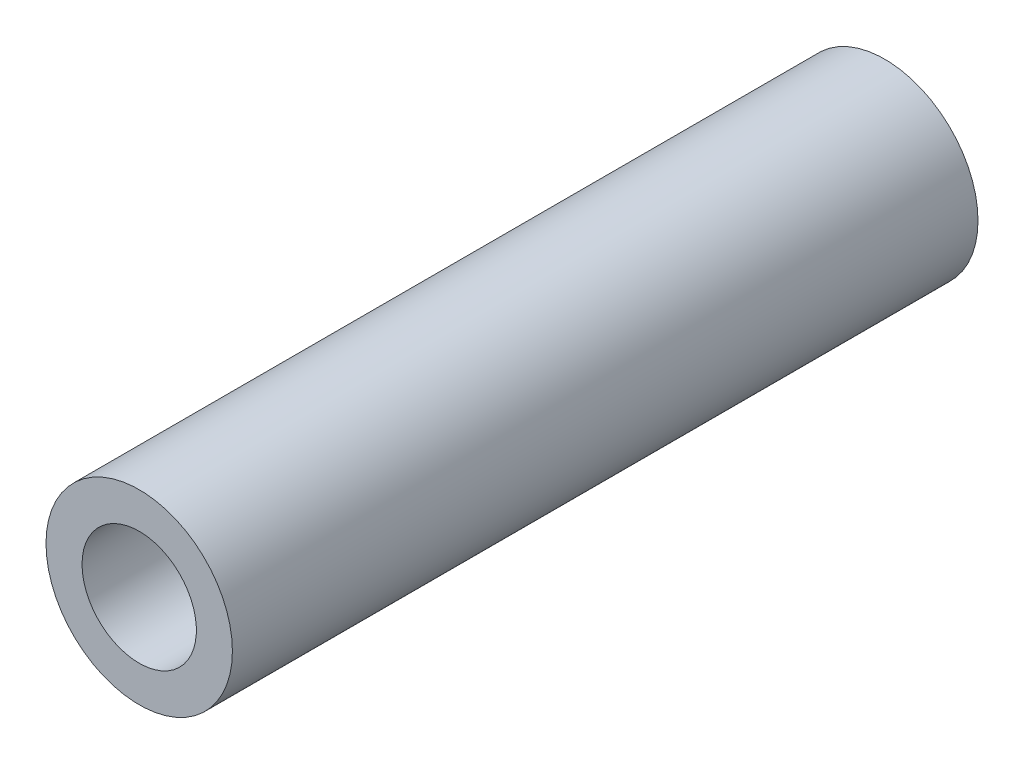
SolidWorks part; units mm, degrees
material "6061-T6 (SS)"
ref_plane "Front Plane" through (0, 0, 0) normal (0, 0, 1) x (1, 0, 0)
ref_plane "Top Plane" through (0, 0, 0) normal (0, 1, 0) x (1, 0, 0)
ref_plane "Right Plane" through (0, 0, 0) normal (1, 0, 0) x (0, 0, -1)
sketch "Sketch1" plane through (0, 0, 0) normal (0, 0, 1) x (1, 0, 0)
  circle A0 centre (0, 0) radius 2.3813
  circle A1 centre (0, 0) radius 1.4605
  dimension "OD" = 4.7625
  dimension "ID" = 2.921
extrude "Extrude1" add sketch "Sketch1" along normal mid plane 19.05
sketch "Sketch2" plane through (0, 0, 0) normal (1, 0, 0) x (0, 0, -1)
  line L0 (-9.525, -1.4605) -> (9.525, -1.4605) construction
  line L3 (9.525, 1.4605) -> (-9.525, 1.4605) construction
  line L5 (-9.525, -1.4605) -> (9.525, -1.4605)
  line L6 (9.525, 1.4605) -> (-9.525, 1.4605)
sketch "Sketch4" plane through (0, 0, 9.525) normal (0, 0, 1) x (1, 0, 0)
  line L0 (0, 0) -> (-1.0327, 1.0327)
  line L1 (0, -2.1828) -> (0, 2.1828) construction
  circle A0 centre (0, 0) radius 1.4605 construction
  dimension "D1" = 45
